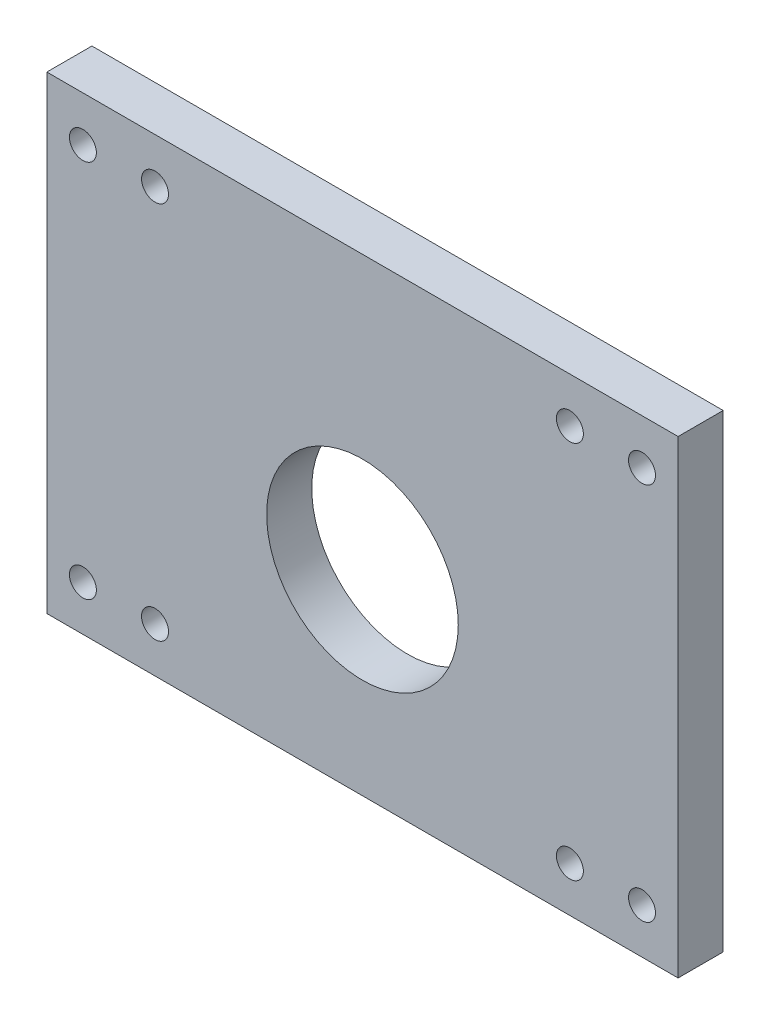
SolidWorks part; units mm, degrees
ref_plane "Front Plane" through (0, 0, 0) normal (0, 0, 1) x (1, 0, 0)
ref_plane "Top Plane" through (0, 0, 0) normal (0, 1, 0) x (1, 0, 0)
ref_plane "Right Plane" through (0, 0, 0) normal (1, 0, 0) x (0, 0, -1)
sketch "Sketch1" plane through (0, 0, 0) normal (0, 0, 1) x (1, 0, 0)
  line L1 (44.45, -33.02) -> (-44.45, -33.02)
  line L2 (44.45, -33.02) -> (44.45, 33.02)
  line L3 (44.45, 33.02) -> (-44.45, 33.02)
  line L4 (-44.45, -33.02) -> (-44.45, 33.02)
  line L5 (44.45, -33.02) -> (-44.45, 33.02) construction
  line L6 (44.45, 33.02) -> (-44.45, -33.02) construction
  circle A1 centre (0, -5.4381) radius 13.4938
  point P0 (0, 0)
  dimension "D5" = 26.9875
  dimension "D1" = 88.9
  dimension "D3" = 66.04
  dimension "D4" = 5.4381
extrude "Boss-Extrude1" add sketch "Sketch1" along normal blind 6.35
hole_wizard "#6 Clearance Hole1" positions "Sketch2" profile "Sketch3" hole size "#6" standard "ANSI Inch" end condition through all
sketch "Sketch2" plane through (0, 0, 6.35) normal (0, 0, 1) x (1, 0, 0)
  line L0 (-39.37, -26.67) -> (-29.21, -26.67)
  line L2 (29.21, -26.67) -> (39.37, -26.67)
  line L4 (-44.45, -33.02) -> (44.45, -33.02) construction
  line L5 (-44.45, 33.02) -> (-44.45, -33.02) construction
  line L6 (44.45, -33.02) -> (44.45, 33.02) construction
  point P0 (-39.37, -26.67)
  point P2 (-29.21, -26.67)
  point P4 (29.21, -26.67)
  point P6 (39.37, -26.67)
  dimension "D1" = 10.16
  dimension "D2" = 10.16
  dimension "D3" = 6.35
  dimension "D4" = 6.35
  dimension "D5" = 5.08
  dimension "D6" = 5.08
sketch "Sketch3" plane through (-39.37, -26.67, 6.35) normal (1, 0, 0) x (0, -1, 0)
  line L0 (0, 0) -> (0, 6.35)
  line L1 (0, 6.35) -> (1.8986, 6.35)
  line L2 (1.8986, 6.35) -> (1.8986, 0)
  line L5 (1.8986, 0) -> (0, 0)
  line L11 (0, -6.35) -> (0, 107.95) construction
  dimension "Thru Hole Dia." = 3.7973
  dimension "Thru Hole Depth" = 6.35
sketch "Sketch4" plane through (0, 0, 6.35) normal (0, 0, 1) x (1, 0, 0)
  line L0 (-44.45, 10.6598) -> (-8.478, 33.02)
  line L1 (-44.45, 33.02) -> (-44.45, -33.02) construction
  line L2 (44.45, 33.02) -> (-44.45, 33.02) construction
  line L5 (-44.45, 10.6598) -> (-44.45, 33.02)
  line L6 (-44.45, 33.02) -> (-8.478, 33.02)
hole_wizard "#6 Clearance Hole2" positions "3DSketch1" profile "Sketch5" hole size "#6" standard "ANSI Inch" end condition through all
sketch3d "3DSketch1"
  line L0 (-39.37, 26.67, 6.35) -> (-29.21, 26.67, 6.35)
  line L2 (29.21, 26.67, 6.35) -> (39.37, 26.67, 6.35)
  line L4 (-44.45, 10.6598, 6.35) -> (-44.45, 33.02, 6.35) construction
  line L5 (44.45, -33.02, 6.35) -> (44.45, 33.02, 6.35) construction
  line L6 (44.45, 33.02, 6.35) -> (-44.45, 33.02, 6.35) construction
  line L7 (-44.45, 33.02, 6.35) -> (-8.478, 33.02, 6.35) construction
  point P0 (-39.37, 26.67, 6.35)
  point P2 (-29.21, 26.67, 6.35)
  point P4 (29.21, 26.67, 6.35)
  point P6 (39.37, 26.67, 6.35)
  dimension "D1" = 10.16
  dimension "D2" = 10.16
  dimension "D3" = 5.08
  dimension "D4" = 5.08
  dimension "D5" = 6.35
  dimension "D6" = 6.35
sketch "Sketch5" plane through (-39.37, 26.67, 6.35) normal (1, 0, 0) x (0, -1, 0)
  line L0 (0, 0) -> (0, 6.35)
  line L1 (0, 6.35) -> (1.8986, 6.35)
  line L2 (1.8986, 6.35) -> (1.8986, 0)
  line L5 (1.8986, 0) -> (0, 0)
  line L11 (0, -6.35) -> (0, 107.95) construction
  dimension "Thru Hole Dia." = 3.7973
  dimension "Thru Hole Depth" = 6.35
